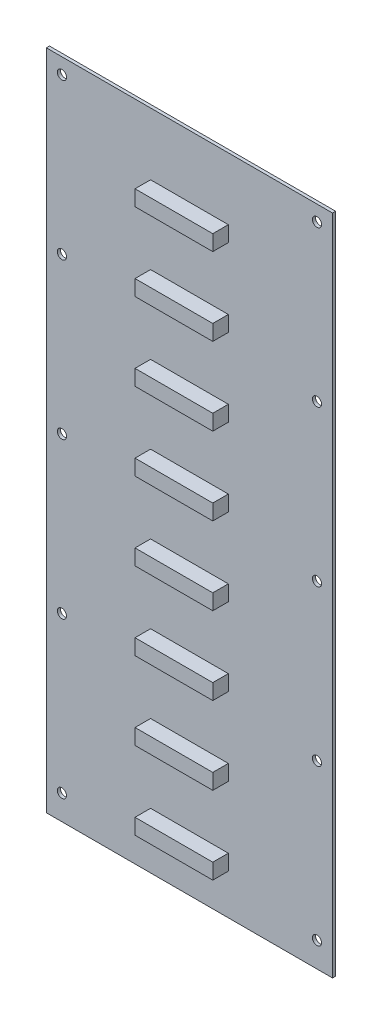
SolidWorks part; units mm, degrees
ref_plane "Front Plane" through (0, 0, 0) normal (0, 0, 1) x (1, 0, 0)
ref_plane "Top Plane" through (0, 0, 0) normal (0, 1, 0) x (1, 0, 0)
ref_plane "Right Plane" through (0, 0, 0) normal (1, 0, 0) x (0, 0, -1)
sketch "Sketch1" plane through (0, 0, 0) normal (0, 0, 1) x (1, 0, 0)
  line L1 (-46, -106.5) -> (46, -106.5)
  line L2 (-46, -106.5) -> (-46, 106.5)
  line L3 (-46, 106.5) -> (46, 106.5)
  line L4 (46, -106.5) -> (46, 106.5)
  line L5 (-46, -106.5) -> (46, 106.5) construction
  line L6 (-46, 106.5) -> (46, -106.5) construction
  point P0 (0, 0)
  dimension "D1" = 92
  dimension "D2" = 213
extrude "Boss-Extrude1" add sketch "Sketch1" along normal blind 1
sketch "Sketch2" plane through (0, 0, 1) normal (0, 0, 1) x (1, 0, 0)
  line L0 (0, -106.5) -> (0, 106.5) construction
  line L1 (-12.5, 81.5) -> (12.5, 81.5)
  line L2 (-12.5, 81.5) -> (-12.5, 86.5)
  line L3 (-12.5, 86.5) -> (12.5, 86.5)
  line L4 (12.5, 81.5) -> (12.5, 86.5)
  line L5 (-12.5, 81.5) -> (12.5, 86.5) construction
  line L6 (-12.5, 86.5) -> (12.5, 81.5) construction
  line L7 (46, 106.5) -> (-46, 106.5) construction
  line L8 (-12.5, 56.5) -> (12.5, 56.5)
  line L9 (-12.5, 56.5) -> (-12.5, 61.5)
  line L10 (-12.5, 61.5) -> (12.5, 61.5)
  line L11 (12.5, 56.5) -> (12.5, 61.5)
  line L12 (-12.5, 56.5) -> (12.5, 61.5) construction
  line L13 (-12.5, 61.5) -> (12.5, 56.5) construction
  line L14 (-12.5, 31.5) -> (12.5, 31.5)
  line L15 (-12.5, 31.5) -> (-12.5, 36.5)
  line L16 (-12.5, 36.5) -> (12.5, 36.5)
  line L17 (12.5, 31.5) -> (12.5, 36.5)
  line L18 (-12.5, 31.5) -> (12.5, 36.5) construction
  line L19 (-12.5, 36.5) -> (12.5, 31.5) construction
  line L20 (-12.5, 6.5) -> (12.5, 6.5)
  line L21 (-12.5, 6.5) -> (-12.5, 11.5)
  line L22 (-12.5, 11.5) -> (12.5, 11.5)
  line L23 (12.5, 6.5) -> (12.5, 11.5)
  line L24 (-12.5, 6.5) -> (12.5, 11.5) construction
  line L25 (-12.5, 11.5) -> (12.5, 6.5) construction
  line L26 (-12.5, -18.5) -> (12.5, -18.5)
  line L27 (-12.5, -18.5) -> (-12.5, -13.5)
  line L28 (-12.5, -13.5) -> (12.5, -13.5)
  line L29 (12.5, -18.5) -> (12.5, -13.5)
  line L30 (-12.5, -18.5) -> (12.5, -13.5) construction
  line L31 (-12.5, -13.5) -> (12.5, -18.5) construction
  line L32 (-12.5, -43.5) -> (12.5, -43.5)
  line L33 (-12.5, -43.5) -> (-12.5, -38.5)
  line L34 (-12.5, -38.5) -> (12.5, -38.5)
  line L35 (12.5, -43.5) -> (12.5, -38.5)
  line L36 (-12.5, -43.5) -> (12.5, -38.5) construction
  line L37 (-12.5, -38.5) -> (12.5, -43.5) construction
  line L38 (-12.5, -68.5) -> (12.5, -68.5)
  line L39 (-12.5, -68.5) -> (-12.5, -63.5)
  line L40 (-12.5, -63.5) -> (12.5, -63.5)
  line L41 (12.5, -68.5) -> (12.5, -63.5)
  line L42 (-12.5, -68.5) -> (12.5, -63.5) construction
  line L43 (-12.5, -63.5) -> (12.5, -68.5) construction
  line L44 (-12.5, -93.5) -> (12.5, -93.5)
  line L45 (-12.5, -93.5) -> (-12.5, -88.5)
  line L46 (-12.5, -88.5) -> (12.5, -88.5)
  line L47 (12.5, -93.5) -> (12.5, -88.5)
  line L48 (-12.5, -93.5) -> (12.5, -88.5) construction
  line L49 (-12.5, -88.5) -> (12.5, -93.5) construction
  point P0 (0, 84)
  point P11 (0, 0)
  point P13 (0, 59)
  point P18 (0, 34)
  point P23 (0, 9)
  point P28 (0, -16)
  point P33 (0, -41)
  point P38 (0, -66)
  point P43 (0, -91)
  dimension "D1" = 25
  dimension "D2" = 5
  dimension "D3" = 20
  dimension "D5" = 20
  dimension "D4" = 8
extrude "Boss-Extrude2" add sketch "Sketch2" along normal blind 5
hole_wizard "#4 Clearance Hole1" positions "Sketch5" profile "Sketch3" hole size "#4" standard "ANSI Inch"
sketch "Sketch5" plane through (0, 0, 1) normal (0, 0, 1) x (1, 0, 0)
  line L0 (0, 0) -> (0, 106.5) construction
  line L1 (46, 106.5) -> (-46, 106.5) construction
  line L3 (-46, 106.5) -> (-46, -106.5) construction
  point P490 (-41, 101.5)
  point P492 (41, 101.5)
  point P508 (-41, 51.5)
  point P509 (41, 51.5)
  point P510 (-41, 1.5)
  point P511 (41, 1.5)
  point P512 (-41, -48.5)
  point P513 (41, -48.5)
  point P514 (-41, -98.5)
  point P515 (41, -98.5)
  dimension "D1" = 5
  dimension "D2" = 5
  dimension "D4" = 50
  dimension "D3" = 5
sketch "Sketch3" plane through (-41, 101.5, 1) normal (1, 0, 0) x (0, -1, 0)
  line L0 (0, 0) -> (0, 4.0602)
  line L1 (0, 4.0602) -> (1.4732, 3.175)
  line L2 (1.4732, 3.175) -> (1.4732, 0)
  line L5 (1.4732, 0) -> (0, 0)
  line L10 (0, 4.0602) -> (-1.4732, 3.175) construction
  line L11 (0, -6.35) -> (0, 107.95) construction
  dimension "Hole Dia." = 2.9464
  dimension "Hole Depth" = 3.175
  dimension "Drill Angle" = 118
